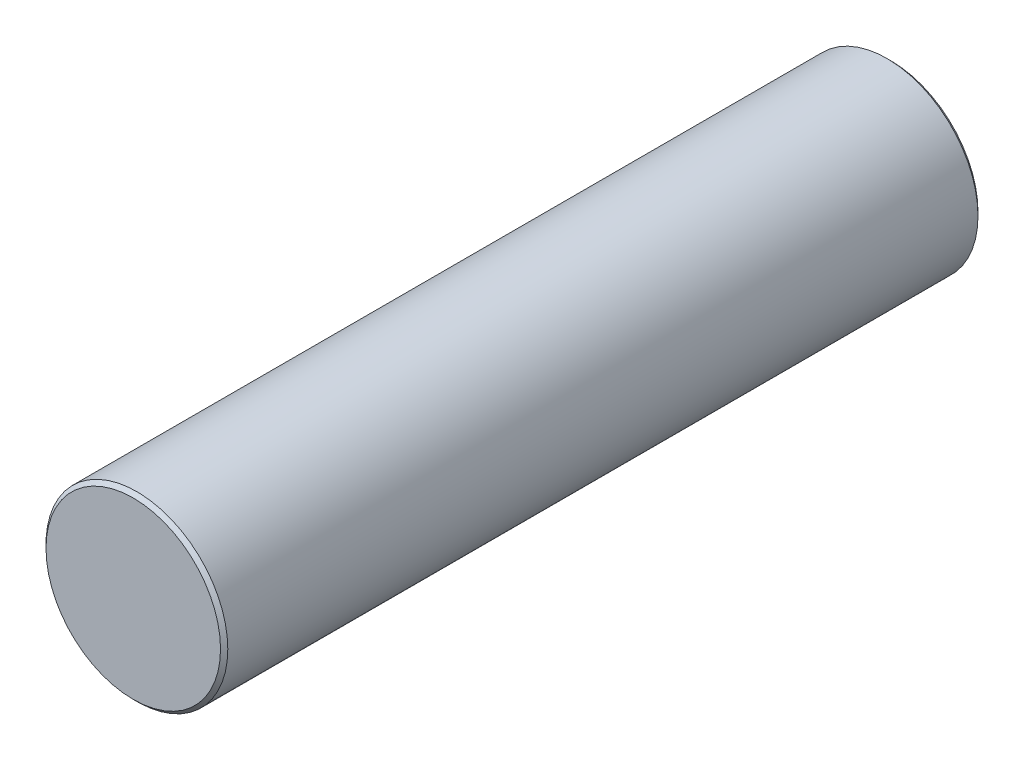
SolidWorks part; units mm, degrees
ref_plane "Front Plane" through (0, 0, 0) normal (0, 0, 1) x (1, 0, 0)
ref_plane "Top Plane" through (0, 0, 0) normal (0, 1, 0) x (1, 0, 0)
ref_plane "Right Plane" through (0, 0, 0) normal (1, 0, 0) x (0, 0, -1)
sketch "Sketch1" plane through (0, 0, 0) normal (1, 0, 0) x (0, 0, -1)
  line L0 (-12.5, 0) -> (12.5, 0) construction
  line L1 (0, -3) -> (0, 3) construction
  point P0 (3.5, 0)
  point P3 (-3.5, 0)
  point P4 (0, 0)
  point P8 (0, 0)
  dimension "Diameter" = 6
  dimension "Length" = 25
  dimension "Break View Space" = 16
  dimension "D2" = 16
sketch "Sketch2" plane through (0, 0, 0) normal (0, 0, 1) x (1, 0, 0)
  circle A0 centre (0, 0) radius 3
extrude "Boss-Extrude1" add sketch "Sketch2" along normal up to vertex (12.5 mm away) and the other way up to vertex (12.5 mm away) up to point (0, 0, 12.5) other way up to point (0, 0, -12.5)
chamfer "Chamfer1" distance 0.12 angle 45 2 edges at (3, 0, -12.5) (3, 0, 12.5)
sketch "Sketch3" plane through (0, 0, 0) normal (0, 0, 1) x (1, 0, 0)
  circle A0 centre (0, 0) radius 3 construction
  circle A1 centre (0, 0) radius 3
  dimension "D1" = 6
equation "\"D1@Chamfer1\"=\"Diameter@Sketch1\"*.02"
equation "\"D2@Sketch1\" = \"Break View Space@Sketch1\""
